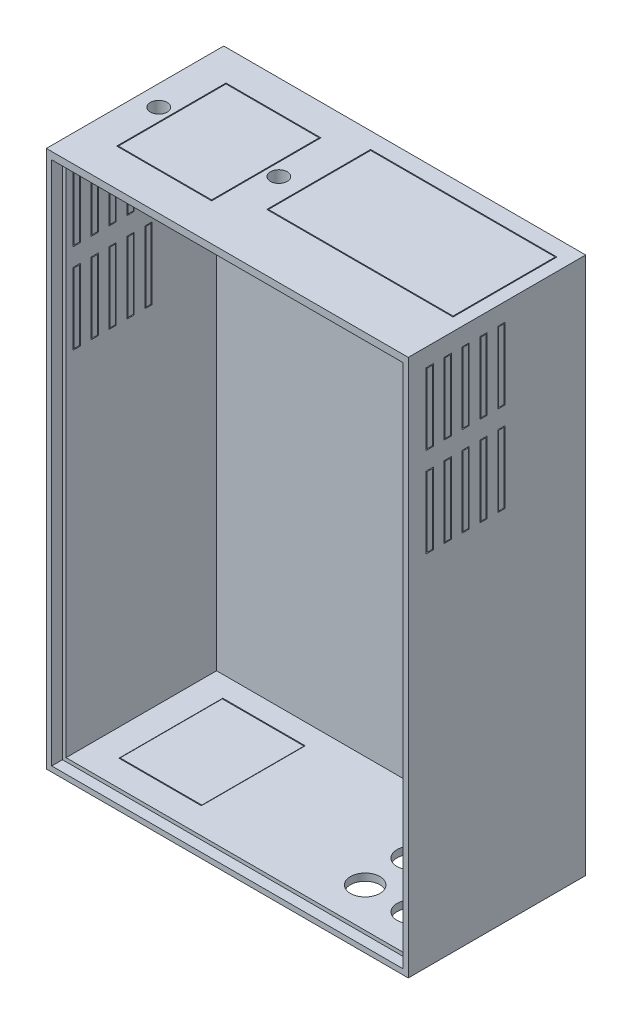
SolidWorks part; units mm, degrees
ref_plane "Front Plane" through (0, 0, 0) normal (0, 0, 1) x (1, 0, 0)
ref_plane "Top Plane" through (0, 0, 0) normal (0, 1, 0) x (1, 0, 0)
ref_plane "Right Plane" through (0, 0, 0) normal (1, 0, 0) x (0, 0, -1)
sketch "Sketch1" plane through (0, 0, 0) normal (0, 0, 1) x (1, 0, 0)
  line L1 (-39.1633, 45.8622) -> (61.8367, 45.8622)
  line L2 (-39.1633, 45.8622) -> (-39.1633, -104.1378)
  line L3 (-39.1633, -104.1378) -> (61.8367, -104.1378)
  line L4 (61.8367, 45.8622) -> (61.8367, -104.1378)
  dimension "D1" = 101
  dimension "D2" = 150
extrude "Boss-Extrude1" add sketch "Sketch1" along normal blind 49.5
sketch "Sketch3" plane through (0, 0, 49.5) normal (0, 0, 1) x (1, 0, 0)
  line L0 (-39.1633, 45.8622) -> (-39.1633, -104.1378) construction
  line L1 (-36.6633, 41.6622) -> (59.3367, 41.6622)
  line L2 (-36.6633, 41.6622) -> (-36.6633, -101.6378)
  line L3 (-36.6633, -101.6378) -> (59.3367, -101.6378)
  line L4 (59.3367, 41.6622) -> (59.3367, -101.6378)
  line L5 (61.8367, -104.1378) -> (61.8367, 45.8622) construction
  line L6 (-39.1633, -104.1378) -> (61.8367, -104.1378) construction
  line L7 (61.8367, 45.8622) -> (-39.1633, 45.8622) construction
  dimension "D1" = 2.5
  dimension "D2" = 2.5
  dimension "D3" = 2.5
  dimension "D4" = 4.2
extrude "Cut-Extrude1" cut sketch "Sketch3" against normal blind 45
sketch "Sketch4" plane through (0, 0, 4.5) normal (0, 0, 1) x (1, 0, 0)
  line L0 (59.3367, -101.6378) -> (59.3367, 41.6622) construction
  line L1 (59.3367, 41.6622) -> (-36.6633, 41.6622) construction
  circle A0 centre (32.9367, 33.6622) radius 1.7
  circle A1 centre (32.9367, -21.3378) radius 1.7
  dimension "D3" = 3.4
  dimension "D6" = 3.4
  dimension "D1" = 26.4
  dimension "D2" = 8
  dimension "D4" = 55
  dimension "D5" = 26.4
extrude "Cut-Extrude2" cut sketch "Sketch4" against normal through all
sketch "Sketch5" plane through (0, 0, 0) normal (0, 0, -1) x (-1, 0, 0)
  circle A0 centre (-32.9367, 33.6622) radius 3.2
  circle A1 centre (-32.9367, -21.3378) radius 3.2
  dimension "D1" = 6.4
  dimension "D2" = 6.4
extrude "Cut-Extrude3" cut sketch "Sketch5" against normal blind 3
sketch "Sketch6" plane through (0, 45.8622, 0) normal (0, 1, 0) x (1, 0, 0)
  line L0 (-39.1633, -49.5) -> (-39.1633, 0) construction
  line L1 (-3.4133, -39.1221) -> (-29.9133, -39.1221)
  line L2 (-3.4133, -39.1221) -> (-3.4133, -8.6221)
  line L3 (-3.4133, -8.6221) -> (-29.9133, -8.6221)
  line L4 (-29.9133, -39.1221) -> (-29.9133, -8.6221)
  dimension "D1" = 26.5
  dimension "D2" = 30.5
  dimension "D3" = 9.25
extrude "Cut-Extrude4" cut sketch "Sketch6" against normal up to vertex (4.2 mm away)
sketch "Sketch7" plane through (0, 45.8622, 0) normal (0, 1, 0) x (1, 0, 0)
  line L7 (-3.4133, -39.1221) -> (-3.4133, -8.6221) construction
  line L8 (-29.9133, -8.6221) -> (-29.9133, -39.1221) construction
  line L9 (-3.4133, -8.6221) -> (-29.9133, -8.6221) construction
  line L10 (-29.9133, -39.1221) -> (-3.4133, -39.1221) construction
  circle A0 centre (0.0867, -23.8721) radius 2.35
  circle A1 centre (-33.4133, -23.8721) radius 2.35
  dimension "D5" = 4.7
  dimension "D6" = 4.7
  dimension "D1" = 3.5
  dimension "D2" = 3.5
  dimension "D3" = 15.25
  dimension "D4" = 15.25
extrude "Cut-Extrude5" cut sketch "Sketch7" against normal up to surface (4.2 mm away) up to face at (-16.6633, 41.6622, 23.8721)
sketch "Sketch8" plane through (0, -104.1378, 0) normal (0, -1, 0) x (1, 0, 0)
  line L1 (-29.1633, 39.25) -> (-6.1633, 39.25)
  line L2 (-29.1633, 39.25) -> (-29.1633, 10.25)
  line L3 (-29.1633, 10.25) -> (-6.1633, 10.25)
  line L4 (-6.1633, 39.25) -> (-6.1633, 10.25)
  line L5 (-39.1633, 0) -> (61.8367, 0) construction
  line L6 (-39.1633, 49.5) -> (-39.1633, 0) construction
  dimension "D1" = 23
  dimension "D2" = 29
  dimension "D3" = 10.25
  dimension "D4" = 10
extrude "Cut-Extrude6" cut sketch "Sketch8" against normal blind 10
sketch "Sketch9" plane through (0, -104.1378, 0) normal (0, -1, 0) x (1, 0, 0)
  line L0 (-29.1633, 39.25) -> (-29.1633, 10.25) construction
  line L1 (-31.6633, 41.75) -> (-3.6633, 41.75)
  line L2 (-31.6633, 41.75) -> (-31.6633, 7.75)
  line L3 (-31.6633, 7.75) -> (-3.6633, 7.75)
  line L4 (-3.6633, 41.75) -> (-3.6633, 7.75)
  line L5 (-6.1633, 10.25) -> (-6.1633, 39.25) construction
  line L6 (-6.1633, 39.25) -> (-29.1633, 39.25) construction
  line L7 (-29.1633, 10.25) -> (-6.1633, 10.25) construction
  dimension "D1" = 2.5
  dimension "D2" = 2.5
  dimension "D3" = 2.5
  dimension "D4" = 2.5
extrude "Cut-Extrude7" cut sketch "Sketch9" against normal blind 1
sketch "Sketch10" plane through (0, -104.1378, 0) normal (0, -1, 0) x (1, 0, 0)
  text T0 "<b>I</b>" font "Century Gothic" height in points 20
extrude "Cut-Extrude8" cut sketch "Sketch10" against normal blind 0.5
sketch "Sketch11" plane through (0, -104.1378, 0) normal (0, -1, 0) x (1, 0, 0)
  text T0 "<b>0</b>" font "Century Gothic" height in points 20
extrude "Cut-Extrude9" cut sketch "Sketch11" against normal blind 0.5
sketch "Sketch12" plane through (-39.1633, 0, 0) normal (-1, 0, 0) x (0, 0, 1)
  line L0 (49.5, -104.1378) -> (49.5, 45.8622) construction
  line L1 (44.5, 40.8622) -> (42.5, 40.8622)
  line L2 (44.5, 40.8622) -> (44.5, 20.8622)
  line L3 (44.5, 20.8622) -> (42.5, 20.8622)
  line L4 (42.5, 40.8622) -> (42.5, 20.8622)
  line L5 (49.5, 45.8622) -> (0, 45.8622) construction
  dimension "D1" = 2
  dimension "D2" = 20
  dimension "D3" = 5
  dimension "D4" = 5
extrude "Cut-Extrude10" cut sketch "Sketch12" against normal through all
pattern_linear "LPattern1" count 5 spacing 5 along (0, 0, -1) count 2 spacing 25 along (0, -1, 0) of "Cut-Extrude10"
sketch "Sketch13" plane through (0, 41.6622, 0) normal (0, -1, 0) x (1, 0, 0)
  line L0 (59.3367, 4.5) -> (-36.6633, 4.5) construction
  line L1 (58.3367, 4.5) -> (6.3367, 4.5)
  line L2 (58.3367, 4.5) -> (58.3367, 33.5)
  line L3 (58.3367, 33.5) -> (6.3367, 33.5)
  line L4 (6.3367, 4.5) -> (6.3367, 33.5)
  line L5 (59.3367, 4.5) -> (59.3367, 49.5) construction
  dimension "D1" = 1
  dimension "D2" = 52
  dimension "D3" = 29
extrude "Cut-Extrude11" cut sketch "Sketch13" against normal blind 10
sketch "Sketch14" plane through (0, -104.1378, 0) normal (0, -1, 0) x (1, 0, 0)
  line L0 (61.8367, 49.5) -> (61.8367, 0) construction
  circle A0 centre (48.8367, 35.5315) radius 4.1
  circle A1 centre (35.8367, 35.5315) radius 4.1
  circle A2 centre (35.8367, 22.5315) radius 4.1
  circle A3 centre (48.8367, 22.5315) radius 4.1
  dimension "D1" = 8.2
  dimension "D2" = 8.2
  dimension "D3" = 8.2
  dimension "D4" = 8.2
  dimension "D5" = 13
  dimension "D6" = 13
  dimension "D7" = 13
  dimension "D8" = 13
  dimension "D9" = 13
extrude "Cut-Extrude12" cut sketch "Sketch14" against normal blind 10
sketch "Sketch15" plane through (0, -104.1378, 0) normal (0, -1, 0) x (1, 0, 0)
  circle A0 centre (35.8367, 35.5315) radius 5.25
  circle A1 centre (48.8367, 35.5315) radius 5.25
  circle A2 centre (35.8367, 22.5315) radius 5.25
  circle A3 centre (48.8367, 22.5315) radius 5.25
  dimension "D1" = 10.5
  dimension "D2" = 10.5
  dimension "D3" = 10.5
  dimension "D4" = 10.5
extrude "Cut-Extrude13" cut sketch "Sketch15" against normal blind 0.5
sketch "Sketch16" plane through (0, 45.8622, 0) normal (0, 1, 0) x (1, 0, 0)
  line L0 (-3.4133, -8.6221) -> (-29.9133, -8.6221) construction
  line L1 (-29.6633, -8.8721) -> (-3.6633, -8.8721)
  line L2 (-29.6633, -8.8721) -> (-29.6633, -38.8721)
  line L3 (-29.6633, -38.8721) -> (-3.6633, -38.8721)
  line L4 (-3.6633, -8.8721) -> (-3.6633, -38.8721)
  line L5 (6.5867, -4.75) -> (58.0867, -4.75)
  line L6 (6.5867, -4.75) -> (6.5867, -33.25)
  line L7 (6.5867, -33.25) -> (58.0867, -33.25)
  line L8 (58.0867, -4.75) -> (58.0867, -33.25)
  line L9 (-29.9133, -8.6221) -> (-29.9133, -39.1221) construction
  line L10 (-3.4133, -39.1221) -> (-3.4133, -8.6221) construction
  line L11 (-29.9133, -39.1221) -> (-3.4133, -39.1221) construction
  line L12 (58.3367, -33.5) -> (6.3367, -33.5) construction
  line L13 (6.3367, -33.5) -> (6.3367, -4.5) construction
  line L14 (58.3367, -4.5) -> (58.3367, -33.5) construction
  line L15 (-36.6633, -4.5) -> (59.3367, -4.5) construction
  dimension "D1" = 0.25
  dimension "D2" = 0.25
  dimension "D3" = 0.25
  dimension "D4" = 0.25
  dimension "D5" = 0.25
  dimension "D6" = 0.25
  dimension "D7" = 0.25
  dimension "D8" = 0.25
extrude "Boss-Extrude2" add sketch "Sketch16" against normal up to surface (4.2 mm away) separate body up to face at (0.0867, 41.6622, 26.2221)
sketch "Sketch17" plane through (0, -103.1378, 0) normal (0, -1, 0) x (1, 0, 0)
  line L0 (-29.1633, 39.25) -> (-6.1633, 39.25) construction
  line L1 (-29.0633, 39) -> (-6.2633, 39)
  line L2 (-29.0633, 39) -> (-29.0633, 10.5)
  line L3 (-29.0633, 10.5) -> (-6.2633, 10.5)
  line L4 (-6.2633, 39) -> (-6.2633, 10.5)
  line L5 (-6.1633, 10.25) -> (-29.1633, 10.25) construction
  line L6 (-29.1633, 10.25) -> (-29.1633, 39.25) construction
  line L7 (-6.1633, 39.25) -> (-6.1633, 10.25) construction
  dimension "D1" = 0.25
  dimension "D2" = 0.25
  dimension "D3" = 0.1
  dimension "D4" = 0.1
extrude "Boss-Extrude3" add sketch "Sketch17" against normal up to surface (1.5 mm away) separate body up to face at (48.8367, -101.6378, 18.4315)
sketch "Sketch18" plane through (-39.1633, 0, 0) normal (-1, 0, 0) x (0, 0, 1)
  line L0 (44.5, 20.8622) -> (44.5, 40.8622) construction
  line L1 (42.75, 40.6122) -> (44.25, 40.6122)
  line L2 (42.75, 40.6122) -> (42.75, 21.1122)
  line L3 (42.75, 21.1122) -> (44.25, 21.1122)
  line L4 (44.25, 40.6122) -> (44.25, 21.1122)
  line L5 (42.5, 40.8622) -> (42.5, 20.8622) construction
  line L6 (44.5, 40.8622) -> (42.5, 40.8622) construction
  line L7 (42.5, 20.8622) -> (44.5, 20.8622) construction
  dimension "D1" = 0.25
  dimension "D2" = 0.25
  dimension "D3" = 0.25
  dimension "D4" = 0.25
extrude "Boss-Extrude4" add sketch "Sketch18" against normal up to surface (2.5 mm away) separate body up to face at (-36.6633, 5.8622, 23.5)
pattern_linear "LPattern2" count 5 spacing 5 along (0, 0, -1) count 2 spacing 25 along (0, -1, 0) of "Boss-Extrude4"
sketch "Sketch19" plane through (61.8367, 0, 0) normal (1, 0, 0) x (0, 0, -1)
  line L0 (-42.5, 40.8622) -> (-42.5, 20.8622) construction
  line L1 (-44.25, 40.6122) -> (-42.75, 40.6122)
  line L2 (-44.25, 40.6122) -> (-44.25, 21.1122)
  line L3 (-44.25, 21.1122) -> (-42.75, 21.1122)
  line L4 (-42.75, 40.6122) -> (-42.75, 21.1122)
  line L5 (-44.5, 20.8622) -> (-44.5, 40.8622) construction
  line L6 (-44.5, 40.8622) -> (-42.5, 40.8622) construction
  line L7 (-42.5, 20.8622) -> (-44.5, 20.8622) construction
  point P8 (-43.5, 40.6122)
  dimension "D1" = 0.25
  dimension "D2" = 0.25
  dimension "D3" = 0.25
  dimension "D4" = 0.25
extrude "Boss-Extrude5" add sketch "Sketch19" against normal up to surface (2.5 mm away) separate body up to face at (59.3367, 5.8622, 23.5)
pattern_linear "LPattern3" count 5 spacing 5 along (0, 0, -1) count 2 spacing 25 along (0, -1, 0) of "Boss-Extrude5"
sketch "Sketch21" plane through (0, 0, 49.5) normal (0, 0, 1) x (1, 0, 0)
  line L0 (61.8367, 45.8622) -> (-39.1633, 45.8622) construction
  line L1 (-37.6633, 43.8622) -> (60.3367, 43.8622)
  line L2 (-37.6633, 43.8622) -> (-37.6633, -102.6378)
  line L3 (-37.6633, -102.6378) -> (60.3367, -102.6378)
  line L4 (60.3367, 43.8622) -> (60.3367, -102.6378)
  line L5 (-39.1633, 45.8622) -> (-39.1633, -104.1378) construction
  line L6 (61.8367, -104.1378) -> (61.8367, 45.8622) construction
  line L7 (-39.1633, -104.1378) -> (61.8367, -104.1378) construction
  dimension "D1" = 2
  dimension "D2" = 1.5
  dimension "D3" = 1.5
  dimension "D4" = 1.5
extrude "Cut-Extrude14" cut sketch "Sketch21" against normal blind 3
sketch "Sketch22" plane through (0, -104.1378, 0) normal (0, -1, 0) x (1, 0, 0)
  text T0 "<b>+</b>" font "Century Gothic" height in points 20
extrude "Cut-Extrude15" cut sketch "Sketch22" against normal blind 0.5
sketch "Sketch23" plane through (0, -104.1378, 0) normal (0, -1, 0) x (1, 0, 0)
  text T0 "<b>-</b>" font "Century Gothic" height in points 25
extrude "Cut-Extrude16" cut sketch "Sketch23" against normal blind 0.5
sketch "Sketch24" plane through (0, -104.1378, 0) normal (0, -1, 0) x (1, 0, 0)
  text T0 "5V" font "Century Gothic" height in points 20
extrude "Cut-Extrude17" cut sketch "Sketch24" against normal blind 0.5
